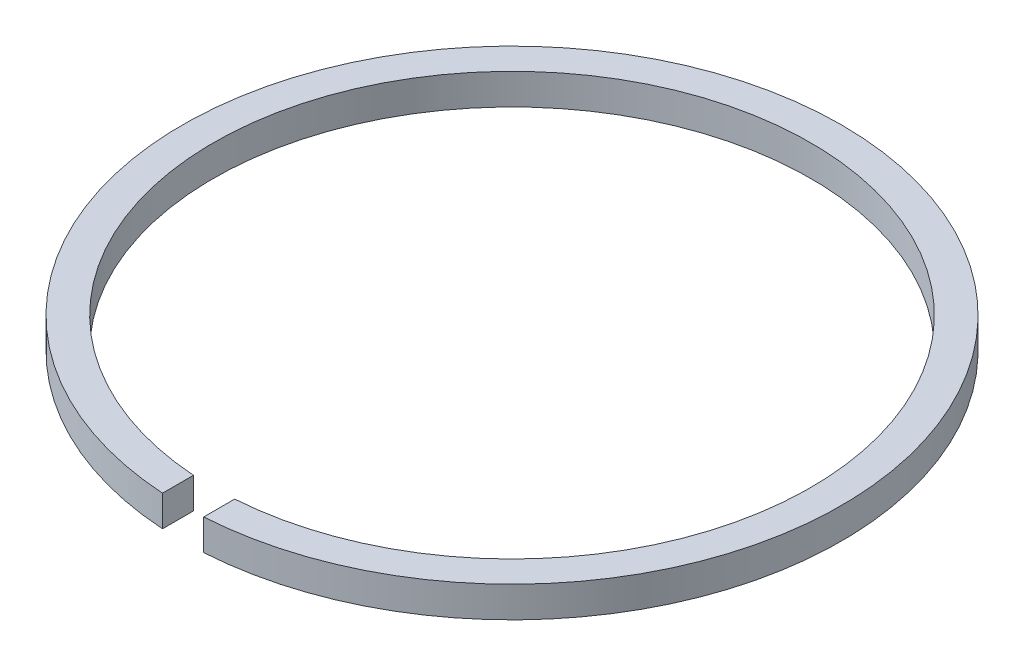
SolidWorks part; units mm, degrees
ref_plane "Front Plane" through (0, 0, 0) normal (0, 0, 1) x (1, 0, 0)
ref_plane "Top Plane" through (0, 0, 0) normal (0, 1, 0) x (1, 0, 0)
ref_plane "Right Plane" through (0, 0, 0) normal (1, 0, 0) x (0, 0, -1)
sketch "Sketch1" plane through (0, 0, 0) normal (0, 1, 0) x (1, 0, 0)
  line L0 (0, 0) -> (0, -16) construction
  line L1 (-1, -14.4655) -> (-1, -15.9687)
  line L2 (-1, 0) -> (-1, -16) construction
  line L3 (1, -14.4655) -> (1, -15.9687)
  circle A0 centre (0, 0) radius 16
  circle A1 centre (0, 0) radius 14.5
  point P7 (-1, -17.1207)
  point P10 (0, 0)
  point P11 (0, 0)
  dimension "D1" = 29
  dimension "D2" = 32
  dimension "D3" = 1
  dimension "D4" = 2
extrude "Boss-Extrude1" add sketch "Sketch1" along normal mid plane 1.5 contours A1 L3 A0 L1
